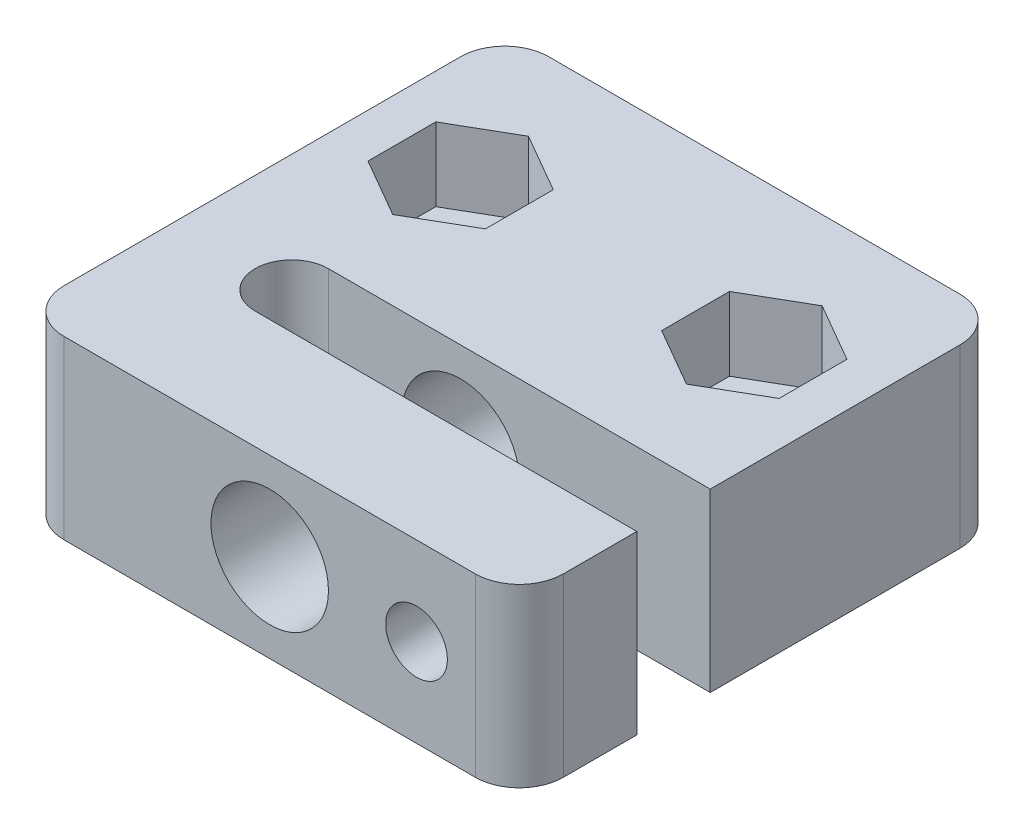
SolidWorks part; units mm, degrees
material "Delrin 2700 NC010, Low Viscosity Acetal Copolymer (SS)"
ref_plane "Front Plane" through (0, 0, 0) normal (0, 0, 1) x (1, 0, 0)
ref_plane "Top Plane" through (0, 0, 0) normal (0, 1, 0) x (1, 0, 0)
ref_plane "Right Plane" through (0, 0, 0) normal (1, 0, 0) x (0, 0, -1)
sketch "Sketch1" plane through (0, 0, 0) normal (0, 0, 1) x (1, 0, 0)
  line L1 (17, -6) -> (-17, -6)
  line L2 (17, -6) -> (17, 6)
  line L3 (17, 6) -> (-17, 6)
  line L4 (-17, -6) -> (-17, 6)
  line L5 (17, -6) -> (-17, 6) construction
  line L6 (17, 6) -> (-17, -6) construction
  point P0 (0, 0)
  dimension "D1" = 12
  dimension "D2" = 34
extrude "Boss-Extrude1" add sketch "Sketch1" along normal mid plane 33
sketch "Sketch2" plane through (0, 0, 16.5) normal (0, 0, 1) x (1, 0, 0)
  circle A0 centre (0, 0) radius 4
  dimension "D1" = 8
extrude "Cut-Extrude1" cut sketch "Sketch2" against normal through all
sketch "Sketch3" plane through (0, 6, 0) normal (0, 1, 0) x (1, 0, 0)
  line L0 (17, 16.5) -> (-17, 16.5) construction
  line L1 (0, -16.5) -> (0, 0) construction
  circle A0 centre (-10, 6.5) radius 2.55
  circle A1 centre (10, 6.5) radius 2.55
  dimension "D1" = 5.1
  dimension "D2" = 20
  dimension "D3" = 10
extrude "Cut-Extrude2" cut sketch "Sketch3" against normal through all
sketch "Sketch4" plane through (0, 6, 0) normal (0, 1, 0) x (1, 0, 0)
  line L0 (0, 0) -> (0, 6.2689) construction
  line L1 (-10, 11.1188) -> (-14, 8.8094)
  line L2 (-14, 8.8094) -> (-14, 4.1906)
  line L3 (-14, 4.1906) -> (-10, 1.8812)
  line L4 (-10, 1.8812) -> (-6, 4.1906)
  line L5 (-6, 4.1906) -> (-6, 8.8094)
  line L6 (-6, 8.8094) -> (-10, 11.1188)
  line L7 (6, 8.8094) -> (10, 11.1188)
  line L8 (6, 4.1906) -> (6, 8.8094)
  line L9 (10, 1.8812) -> (6, 4.1906)
  line L10 (14, 4.1906) -> (10, 1.8812)
  line L11 (14, 8.8094) -> (14, 4.1906)
  line L12 (10, 11.1188) -> (14, 8.8094)
  circle A0 centre (-10, 6.5) radius 4 construction
  circle A1 centre (10, 6.5) radius 4 construction
  dimension "D1" = 8
extrude "Cut-Extrude3" cut sketch "Sketch4" against normal blind 5
sketch "Sketch5" plane through (0, -6, 0) normal (0, -1, 0) x (1, 0, 0)
  circle A0 centre (10, -6.5) radius 4.5
  circle A1 centre (-10, -6.5) radius 4.5
  dimension "D1" = 9
extrude "Cut-Extrude4" cut sketch "Sketch5" against normal blind 2
sketch "Sketch6" plane through (0, 6, 0) normal (0, 1, 0) x (1, 0, 0)
  line L0 (17, -6) -> (-9, -6) construction
  line L1 (17, -16.5) -> (17, 16.5) construction
  line L2 (17, -8.5) -> (-9, -8.5)
  line L3 (17, -3.5) -> (-9, -3.5)
  line L4 (17, -16.5) -> (-17, -16.5) construction
  arc A0 (17, -8.5) -> (17, -3.5) centre (17, -6) ccw
  arc A1 (-9, -3.5) -> (-9, -8.5) centre (-9, -6) ccw
  point P4 (4, -6)
  dimension "D1" = 5
  dimension "D2" = 8
  dimension "D3" = 26
extrude "Cut-Extrude5" cut sketch "Sketch6" against normal through all
hole_wizard "M5x0.8 Tapped Hole1" positions "Sketch8" profile "Sketch7" tap size "M5x0.8" standard "ANSI Metric"
sketch "Sketch8" plane through (0, 0, 16.5) normal (0, 0, 1) x (1, 0, 0)
  line L0 (10, 0) -> (0, 0) construction
  point P0 (10, 0)
  dimension "D1" = 10
sketch "Sketch7" plane through (10, 0, 16.5) normal (1, 0, 0) x (0, -1, 0)
  line L0 (0, 0) -> (0, 8)
  line L1 (0, 8) -> (2.1, 8)
  line L2 (2.1, 8) -> (2.1, 0)
  line L5 (2.1, 0) -> (0, 0)
  line L11 (0, -6.35) -> (0, 107.95) construction
  dimension "Thread Major Dia." = 4.2
  dimension "Thru Tap Drill Depth" = 8
fillet "Fillet1" radius 3 4 edges at (-17, 0, -16.5) (17, 0, -16.5) (17, 0, 16.5) (-17, 0, 16.5)
